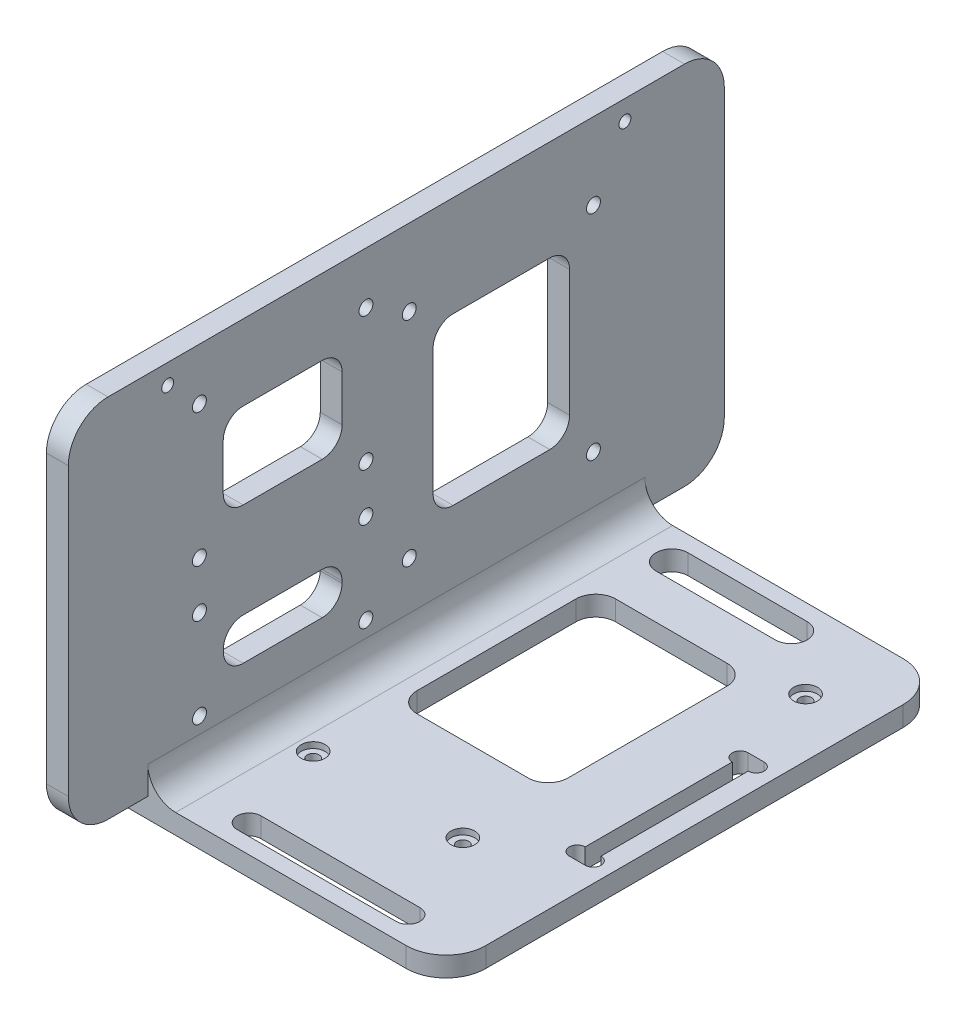
SolidWorks part; units mm, degrees
ref_plane "前视基准面" through (0, 0, 0) normal (0, 0, 1) x (1, 0, 0)
ref_plane "上视基准面" through (0, 0, 0) normal (0, 1, 0) x (1, 0, 0)
ref_plane "右视基准面" through (0, 0, 0) normal (1, 0, 0) x (0, 0, -1)
other "Configuration Table"
sketch "草图1" plane through (0, 0, 0) normal (1, 0, 0) x (0, 0, -1)
  line L0 (-33.925, 69.765) -> (-33.925, -22.26)
  line L1 (-20.925, 11.26) -> (20.925, 11.26) construction
  line L2 (-20.925, 11.26) -> (-20.925, -11.26) construction
  line L3 (-20.925, -11.26) -> (20.925, -11.26) construction
  line L4 (20.925, 11.26) -> (20.925, -11.26) construction
  line L5 (-20.925, 11.26) -> (20.925, -11.26) construction
  line L6 (-20.925, -11.26) -> (20.925, 11.26) construction
  line L7 (-20.955, 56.765) -> (20.955, 56.765) construction
  line L8 (-20.955, 56.765) -> (-20.955, 23.235) construction
  line L9 (-20.955, 23.235) -> (20.955, 23.235) construction
  line L10 (20.955, 56.765) -> (20.955, 23.235) construction
  line L11 (-20.955, 56.765) -> (20.955, 23.235) construction
  line L12 (-20.955, 23.235) -> (20.955, 56.765) construction
  line L13 (31.835, 50.47) -> (78.165, 50.47) construction
  line L14 (31.835, 50.47) -> (31.835, -3.26) construction
  line L15 (31.835, -3.26) -> (78.165, -3.26) construction
  line L16 (78.165, 50.47) -> (78.165, -3.26) construction
  line L17 (31.835, 50.47) -> (78.165, -3.26) construction
  line L18 (31.835, -3.26) -> (78.165, 50.47) construction
  line L19 (-33.925, 69.765) -> (91.075, 69.765)
  line L20 (-33.925, -22.26) -> (91.075, -22.26)
  line L21 (91.075, 69.765) -> (91.075, -22.26)
  line L22 (-14.955, 50.765) -> (14.955, 50.765)
  line L23 (14.955, 50.765) -> (14.955, 29.235)
  line L24 (-14.955, 29.235) -> (14.955, 29.235)
  line L25 (-14.955, 50.765) -> (-14.955, 29.235)
  line L26 (-14.925, 5.26) -> (-14.925, -5.26)
  line L27 (-14.925, -5.26) -> (14.925, -5.26)
  line L28 (14.925, 5.26) -> (14.925, -5.26)
  line L29 (-14.925, 5.26) -> (14.925, 5.26)
  line L30 (37.835, 44.47) -> (37.835, 2.74)
  line L31 (37.835, 2.74) -> (72.165, 2.74)
  line L32 (72.165, 44.47) -> (72.165, 2.74)
  line L33 (37.835, 44.47) -> (72.165, 44.47)
  circle A0 centre (-20.925, 11.26) radius 1.75
  circle A1 centre (20.925, 11.26) radius 1.75
  circle A2 centre (20.925, -11.26) radius 1.75
  circle A3 centre (-20.925, -11.26) radius 1.75
  circle A4 centre (-20.955, 56.765) radius 1.75
  circle A5 centre (20.955, 56.765) radius 1.75
  circle A6 centre (20.955, 23.235) radius 1.75
  circle A7 centre (-20.955, 23.235) radius 1.75
  circle A8 centre (31.835, 50.47) radius 1.75
  circle A9 centre (78.165, 50.47) radius 1.75
  circle A10 centre (78.165, -3.26) radius 1.75
  circle A11 centre (31.835, -3.26) radius 1.75
  circle A12 centre (-28.925, 64.765) radius 1.5
  circle A15 centre (86.075, 64.765) radius 1.5
  point P0 (0, 0)
  point P10 (0, 40)
  point P21 (55, 23.605)
  dimension "D1" = 3.5
  dimension "D6" = 3.5
  dimension "D11" = 3.5
  dimension "D14" = 3
  dimension "D2" = 41.85
  dimension "D3" = 22.52
  dimension "D4" = 41.91
  dimension "D5" = 33.53
  dimension "D7" = 40
  dimension "D8" = 46.33
  dimension "D9" = 53.73
  dimension "D10" = 55
  dimension "D12" = 8
  dimension "D13" = 125
  dimension "D15" = 13
  dimension "D16" = 5
  dimension "D17" = 5
  dimension "D18" = 11
  dimension "D21" = 13
  dimension "D22" = 5
  dimension "D23" = 5
  dimension "D26" = 6
extrude "凸台-拉伸1" add sketch "草图1" along normal blind 5.5
fillet "圆角1" radius 5 12 edges at (2.75, 44.47, -37.835) (2.75, 2.74, -37.835) (2.75, 2.74, -72.165) (2.75, 44.47, -72.165) (2.75, 29.235, 14.955) (2.75, 29.235, -14.955) (2.75, 5.26, 14.925) (2.75, -5.26, 14.925) (2.75, -5.26, -14.925) (2.75, 5.26, -14.925) (2.75, 50.765, -14.955) (2.75, 50.765, 14.955)
sketch "草图2" plane through (0, 0, 0) normal (-1, 0, 0) x (0, 0, 1)
  circle A1 centre (28.925, 64.765) radius 1.5 construction
  circle A2 centre (-86.075, 64.765) radius 1.5 construction
  circle A5 centre (28.925, 64.765) radius 1.5
  circle A6 centre (-86.075, 64.765) radius 1.5
  circle A13 centre (20.925, 11.26) radius 1.75
  circle A14 centre (20.925, 11.26) radius 1.75
  circle A15 centre (-20.925, 11.26) radius 1.75
  circle A16 centre (-20.925, 11.26) radius 1.75
  circle A17 centre (-20.925, -11.26) radius 1.75
  circle A18 centre (-20.925, -11.26) radius 1.75
  circle A19 centre (20.925, -11.26) radius 1.75
  circle A20 centre (20.925, -11.26) radius 1.75
  circle A21 centre (20.955, 56.765) radius 1.75
  circle A22 centre (20.955, 56.765) radius 1.75
  circle A23 centre (-20.955, 56.765) radius 1.75
  circle A24 centre (-20.955, 56.765) radius 1.75
  circle A25 centre (-20.955, 23.235) radius 1.75
  circle A26 centre (-20.955, 23.235) radius 1.75
  circle A27 centre (20.955, 23.235) radius 1.75
  circle A28 centre (20.955, 23.235) radius 1.75
  circle A29 centre (-78.165, 50.47) radius 1.75
  circle A30 centre (-78.165, 50.47) radius 1.75
  circle A31 centre (-31.835, 50.47) radius 1.75
  circle A32 centre (-31.835, 50.47) radius 1.75
  circle A33 centre (-78.165, -3.26) radius 1.75
  circle A34 centre (-78.165, -3.26) radius 1.75
  circle A35 centre (-31.835, -3.26) radius 1.75
  circle A36 centre (-31.835, -3.26) radius 1.75
  circle A37 centre (28.925, 64.765) radius 1.5
  circle A38 centre (28.925, 64.765) radius 1.5
  circle A39 centre (-86.075, 64.765) radius 1.5
  circle A40 centre (-86.075, 64.765) radius 1.5
  circle A41 centre (28.925, 64.765) radius 3
  circle A42 centre (-86.075, 64.765) radius 3
  circle A43 centre (20.925, 11.26) radius 3.25
  circle A68 centre (-20.925, 11.26) radius 3.25
  circle A69 centre (-20.925, -11.26) radius 3.25
  circle A70 centre (20.925, -11.26) radius 3.25
  circle A71 centre (20.955, 56.765) radius 3.25
  circle A72 centre (-20.955, 56.765) radius 3.25
  circle A73 centre (-20.955, 23.235) radius 3.25
  circle A74 centre (20.955, 23.235) radius 3.25
  circle A75 centre (-78.165, 50.47) radius 3.25
  circle A76 centre (-31.835, 50.47) radius 3.25
  circle A77 centre (-78.165, -3.26) radius 3.25
  circle A78 centre (-31.835, -3.26) radius 3.25
  circle A79 centre (28.925, 64.765) radius 3
  circle A80 centre (-86.075, 64.765) radius 3
  circle M3 centre (-86.075, 64.765) radius 1.5
  circle M4 centre (28.925, 64.765) radius 1.5
  circle M5 centre (-78.165, -3.26) radius 1.75
  circle M6 centre (-78.165, 50.47) radius 1.75
  circle M7 centre (-20.955, 23.235) radius 1.75
  circle M8 centre (20.955, 56.765) radius 1.75
  circle M9 centre (-20.925, -11.26) radius 1.75
  circle M10 centre (20.925, 11.26) radius 1.75
  circle M18 centre (-20.925, 11.26) radius 1.75
  circle M19 centre (20.925, -11.26) radius 1.75
  circle M21 centre (20.955, 23.235) radius 1.75
  circle M22 centre (-31.835, 50.47) radius 1.75
  circle M23 centre (-31.835, -3.26) radius 1.75
  dimension "D2" = 0
  dimension "D3" = 0
  dimension "D4" = 0
  dimension "D5" = 0
  dimension "D6" = 0
  dimension "D7" = 0
  dimension "D8" = 0
  dimension "D9" = 0
  dimension "D10" = 0
  dimension "D11" = 0
  dimension "D12" = 0
  dimension "D13" = 0
  dimension "D14" = 0
  dimension "D15" = 0
  dimension "D16" = 1.5
extrude "切除-拉伸1" cut sketch "草图2" against normal blind 2 contours A42 M3 | A75 M6 | A76 M22 | A77 M5 | A78 M23 | A69 M9 | A73 M7 | A68 M18 | A71 M8 | A41 M4 | A74 M21 | A43 M10 | A70 M19 | A72
sketch "草图3" plane through (0, -22.26, 0) normal (0, -1, 0) x (1, 0, 0)
  line L0 (80.5, 33.925) -> (-6, 33.925)
  line L1 (80.5, 33.925) -> (80.5, -91.075)
  line L2 (-6, 33.925) -> (-6, -91.075)
  line L3 (80.5, -91.075) -> (-6, -91.075)
  line L4 (0, 33.925) -> (0, -91.075)
  line L5 (0, -91.075) -> (5.5, -91.075)
  line L6 (5.5, -91.075) -> (5.5, 33.925)
  line L7 (5.5, 33.925) -> (0, 33.925)
  line L8 (0, 33.925) -> (0, -91.075)
  line L9 (0, -91.075) -> (5.5, -91.075)
  line L10 (5.5, -91.075) -> (5.5, 33.925)
  line L11 (5.5, 33.925) -> (0, 33.925)
  line L12 (73.5, -28.575) -> (80.5, -28.575) construction
  line L13 (16.5, 3.335) -> (54.15, 3.335) construction
  line L14 (63.9619, 26.925) -> (23.9619, 26.925) construction
  line L17 (54.325, -17.9224) -> (16.325, -17.9224)
  line L18 (71.5, -6.075) -> (75.5, -6.075)
  line L19 (71.5, -6.075) -> (71.5, -51.075)
  line L20 (71.5, -51.075) -> (75.5, -51.075)
  line L21 (75.5, -6.075) -> (75.5, -51.075)
  line L22 (71.5, -6.075) -> (75.5, -51.075) construction
  line L23 (71.5, -51.075) -> (75.5, -6.075) construction
  line L24 (54.325, -17.9224) -> (54.325, -67.9224)
  line L25 (54.325, -67.9224) -> (16.325, -67.9224)
  line L26 (16.325, -17.9224) -> (16.325, -67.9224)
  line L27 (54.325, -17.9224) -> (16.325, -67.9224) construction
  line L28 (54.325, -67.9224) -> (16.325, -17.9224) construction
  line L29 (63.9619, 23.925) -> (23.9619, 23.925)
  line L30 (63.9619, 29.925) -> (23.9619, 29.925)
  line L31 (50.325, -83.075) -> (20.325, -83.075) construction
  line L32 (50.325, -87.075) -> (20.325, -87.075)
  line L33 (50.325, -79.075) -> (20.325, -79.075)
  circle A4 centre (71.5, -8.075) radius 2
  circle A5 centre (75.5, -8.075) radius 2
  circle A6 centre (75.5, -49.075) radius 2
  circle A7 centre (71.5, -49.075) radius 2
  circle A9 centre (65.94, -71.075) radius 1.5
  circle A10 centre (5.14, -71.075) radius 1.5 construction
  circle A11 centre (54.15, 3.335) radius 1.5
  circle A12 centre (16.5, 3.335) radius 1.5
  arc A13 (63.9619, 23.925) -> (63.9619, 29.925) centre (63.9619, 26.925) ccw
  arc A14 (23.9619, 29.925) -> (23.9619, 23.925) centre (23.9619, 26.925) ccw
  arc A15 (50.325, -87.075) -> (50.325, -79.075) centre (50.325, -83.075) ccw
  arc A16 (20.325, -79.075) -> (20.325, -87.075) centre (20.325, -83.075) ccw
  point P14 (35.325, 3.335)
  point P19 (43.9619, 26.925)
  point P23 (73.5, -28.575)
  point P35 (35.325, -42.9224)
  point P46 (35.325, -83.075)
  point P51 (35.325, -83.075)
  dimension "D4" = 37.65
  dimension "D5" = 74.41
  dimension "D9" = 60.8
  dimension "D14" = 4
  dimension "D15" = 4
  dimension "D3" = 3
  dimension "D20" = 3
  dimension "D23" = 4
  dimension "D2" = 6
  dimension "D6" = 11.79
  dimension "D7" = 75
  dimension "D8" = 2
  dimension "D10" = 11
  dimension "D11" = 4
  dimension "D12" = 66
  dimension "D13" = 45
  dimension "D16" = 20
  dimension "D17" = 50
  dimension "D18" = 38
  dimension "D19" = 4
  dimension "D21" = 40
  dimension "D22" = 4
  dimension "D24" = 30
  dimension "D1" = 0
extrude "凸台-拉伸2" add sketch "草图3" along normal blind 5
sketch "草图6" plane through (0, -22.26, 0) normal (0, 1, 0) x (1, 0, 0)
  circle A6 centre (65.94, 71.075) radius 1.5 construction
  circle A7 centre (54.15, -3.335) radius 1.5 construction
  circle A8 centre (16.5, -3.335) radius 1.5 construction
  circle A9 centre (65.94, 71.075) radius 1.5
  circle A10 centre (54.15, -3.335) radius 1.5
  circle A11 centre (16.5, -3.335) radius 1.5
  circle A12 centre (65.94, 71.075) radius 3
  circle A13 centre (54.15, -3.335) radius 3
  circle A14 centre (16.5, -3.335) radius 3
  dimension "D1" = 1.5
extrude "切除-拉伸2" cut sketch "草图6" against normal blind 1.5
fillet "圆角3" radius 7 1 edges at (5.5, -22.26, -28.575)
fillet "圆角4" radius 10 2 edges at (80.5, -24.76, -91.075) (80.5, -24.76, 33.925)
sketch "草图7" plane through (0, 0, 33.925) normal (0, 0, 1) x (1, 0, 0)
  line L1 (0, -22.26) -> (5.5, -22.26)
  line L2 (0, -22.26) -> (0, 69.765)
  line L3 (0, 69.765) -> (5.5, 69.765)
  line L4 (5.5, -22.26) -> (5.5, 69.765)
extrude "凸台-拉伸5" add sketch "草图7" along normal blind 20
fillet "圆角6" radius 5 6 edges at (-6, -24.76, 33.925) (-6, -24.76, -91.075) (16.325, -24.76, -67.9224) (54.325, -24.76, -67.9224) (16.325, -24.76, -17.9224) (54.325, -24.76, -17.9224)
sketch "草图8" plane through (0, 0, -91.075) normal (0, 0, -1) x (-1, 0, 0)
  line L0 (0, -22.26) -> (-5.5, -22.26)
  line L1 (-5.5, -22.26) -> (-5.5, -15.26)
  line L8 (-70.5, -27.26) -> (1, -27.26)
  line L9 (1, -27.26) -> (1, -22.26)
  line L10 (1, -22.26) -> (0, -22.26)
  line L11 (0, -22.26) -> (0, 69.765)
  line L12 (0, 69.765) -> (-5.5, 69.765)
  line L13 (-5.5, 69.765) -> (-5.5, -15.26)
  line L14 (-12.5, -22.26) -> (-70.5, -22.26)
  line L15 (-70.5, -22.26) -> (-70.5, -27.26)
  line L16 (-70.5, -27.26) -> (1, -27.26)
  line L17 (1, -27.26) -> (1, -22.26)
  line L18 (1, -22.26) -> (0, -22.26)
  line L19 (0, -22.26) -> (0, 69.765)
  line L20 (0, 69.765) -> (-5.5, 69.765)
  line L21 (-5.5, 69.765) -> (-5.5, -15.26)
  line L22 (-12.5, -22.26) -> (-70.5, -22.26)
  line L23 (-70.5, -22.26) -> (-70.5, -27.26)
  arc A1 (-12.5, -22.26) -> (-5.5, -15.26) centre (-12.5, -15.26) ccw
  arc A2 (-12.5, -22.26) -> (-5.5, -15.26) centre (-12.5, -15.26) ccw
  line M13 (0, -22.26) -> (0, 69.765)
  line M14 (0, 69.765) -> (-5.5, 69.765)
  line M15 (-5.5, 69.765) -> (-5.5, -15.26)
  dimension "D1" = 0
extrude "凸台-拉伸6" add sketch "草图8" along normal blind 20 contours L1 L0 M13 M14 M15
fillet "圆角5" radius 10 4 edges at (2.75, -22.26, 53.925) (2.75, 69.765, 53.925) (2.75, -22.26, -111.075) (2.75, 69.765, -111.075)
